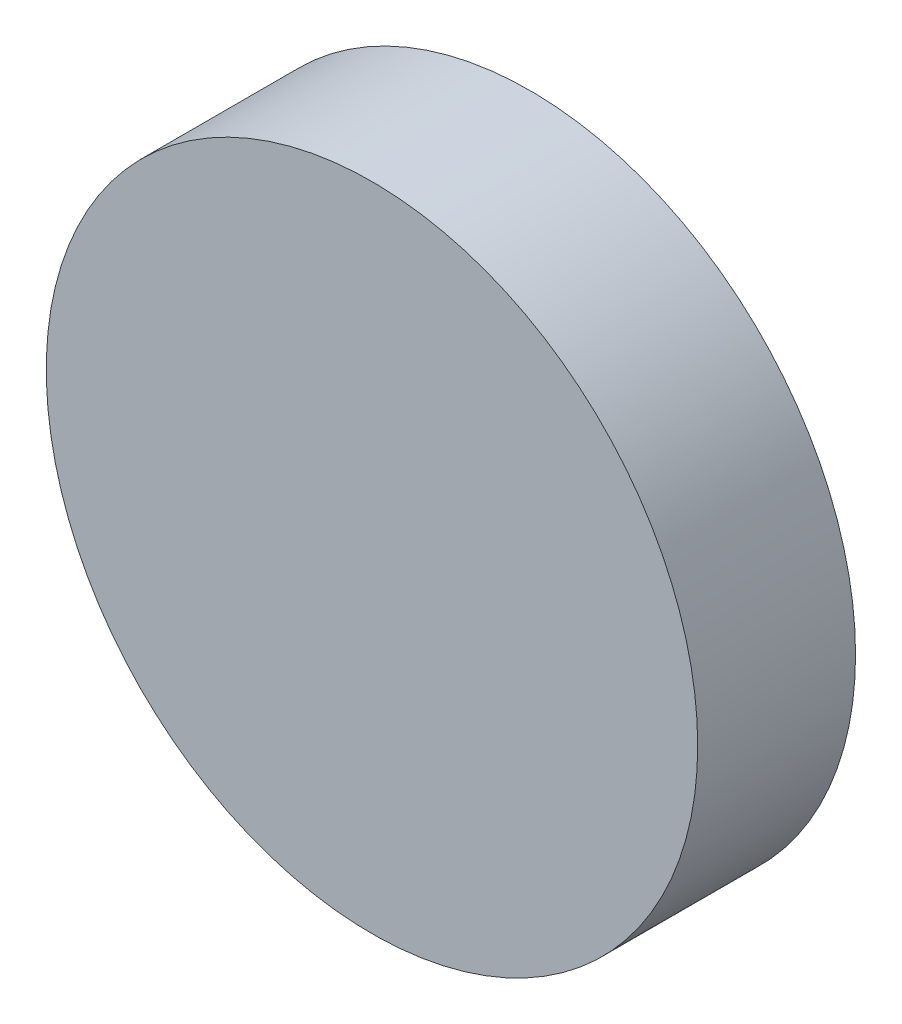
SolidWorks part; units mm, degrees
ref_plane "Plan de face" through (0, 0, 0) normal (0, 0, 1) x (1, 0, 0)
ref_plane "Plan de dessus" through (0, 0, 0) normal (0, 1, 0) x (1, 0, 0)
ref_plane "Plan de droite" through (0, 0, 0) normal (1, 0, 0) x (0, 0, -1)
sketch "Esquisse1" plane through (0, 0, 0) normal (0, 0, 1) x (1, 0, 0)
  circle A0 centre (41.5, 31.275) radius 41.275
extrude "Boss.-Extru.1" add sketch "Esquisse1" along normal blind 20
